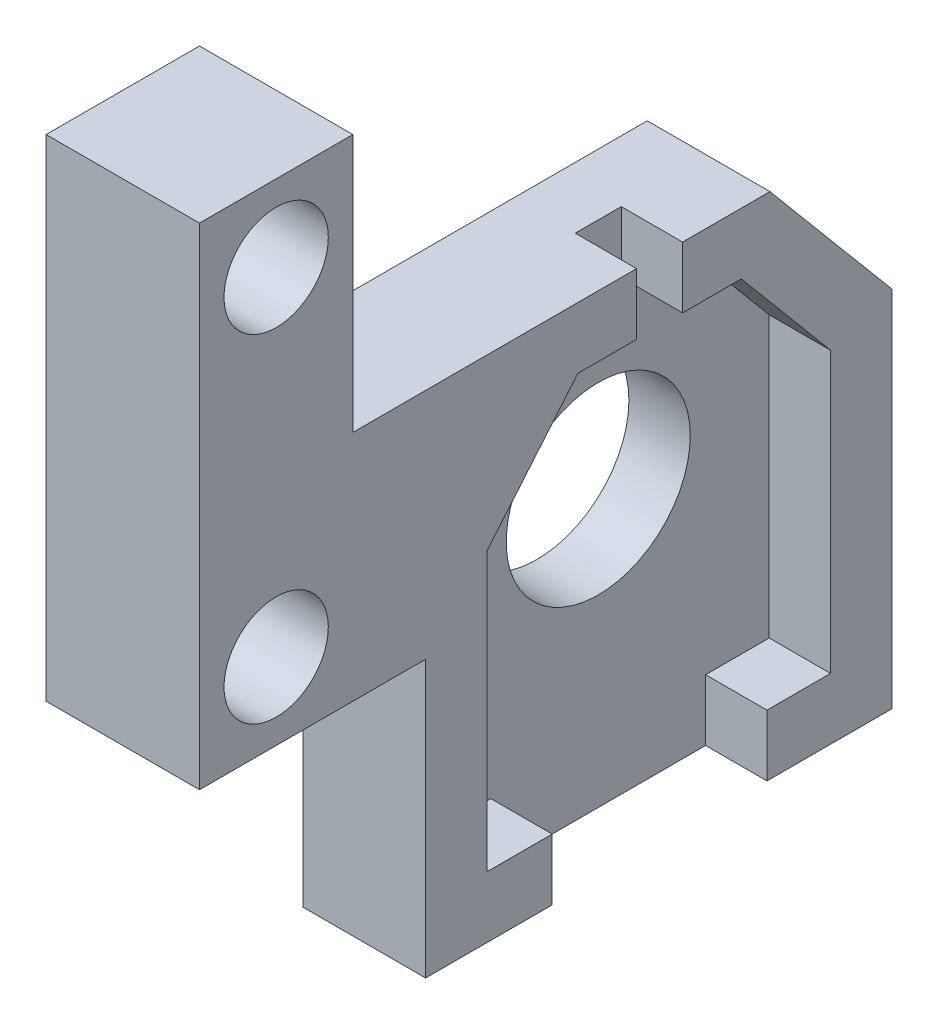
SolidWorks part; units mm, degrees
ref_plane "Front Plane" through (0, 0, 0) normal (0, 0, 1) x (1, 0, 0)
ref_plane "Top Plane" through (0, 0, 0) normal (0, 1, 0) x (1, 0, 0)
ref_plane "Right Plane" through (0, 0, 0) normal (1, 0, 0) x (0, 0, -1)
sketch "Sketch1" plane through (0, 0, 0) normal (1, 0, 0) x (0, 0, -1)
  line L0 (-6.1093, 3.9687) -> (-3.1473, 7.4987)
  line L1 (-3.1473, 7.4987) -> (-1.2321, 7.4987)
  line L2 (-6.1093, 3.9687) -> (-6.1093, -5.0913)
  line L3 (-6.1093, -5.0913) -> (-3.9821, -5.0913)
  line L4 (5.0907, 4.0335) -> (5.0907, -5.0913)
  line L5 (-4.0799, 9.4987) -> (-1.2321, 9.4987)
  line L6 (-8.1093, 4.6966) -> (-8.1093, -7.0913)
  line L7 (-8.1093, -7.0913) -> (-3.9821, -7.0913)
  line L8 (7.0907, 4.7614) -> (7.0907, -7.0913)
  line L9 (5.0907, 4.0335) -> (2.1831, 7.4987)
  line L10 (-8.1093, 4.6966) -> (-4.0799, 9.4987)
  line L11 (3.1157, 9.4987) -> (7.0907, 4.7614)
  line L12 (0.2679, 7.4987) -> (0.2679, 9.4987)
  line L13 (-1.2321, 7.4987) -> (-1.2321, 9.4987)
  line L14 (3.0179, -5.0913) -> (3.0179, -7.0913)
  line L15 (-3.9821, -5.0913) -> (-3.9821, -7.0913)
  line L16 (-0.4821, 1.9087) -> (-0.4821, -6.5913) construction
  line L17 (-8.1093, 1.9087) -> (7.0907, 1.9087) construction
  line L18 (0.2679, 9.4987) -> (3.1157, 9.4987)
  line L19 (0.2679, 7.4987) -> (2.1831, 7.4987)
  line L20 (3.0179, -5.0913) -> (5.0907, -5.0913)
  line L21 (3.0179, -7.0913) -> (7.0907, -7.0913)
  point P20 (1.2255, 7.4987)
  dimension "D1" = 2
  dimension "D2" = 2
  dimension "D3" = 2
  dimension "D4" = 2
  dimension "D5" = 2
  dimension "D6" = 2
  dimension "D7" = 40
  dimension "D8" = 40
  dimension "D9" = 3.53
  dimension "D10" = 3.5
  dimension "D11" = 7
  dimension "D12" = 3.5
  dimension "D13" = 0.75
  dimension "D14" = 0.75
  dimension "D15" = 5.59
  dimension "D16" = 11.2
sketch "Sketch2" plane through (0, 0, 0) normal (1, 0, 0) x (0, 0, -1)
  line L0 (-8.1093, -7.0913) -> (-8.1093, 4.6966)
  line L1 (-8.1093, 4.6966) -> (-4.0799, 9.4987)
  line L2 (-4.0799, 9.4987) -> (3.1157, 9.4987)
  line L3 (3.1157, 9.4987) -> (7.0907, 4.7614)
  line L4 (7.0907, 4.7614) -> (7.0907, -7.0913)
  line L5 (7.0907, -7.0913) -> (-8.1093, -7.0913)
extrude "Boss-Extrude1" add sketch "Sketch2" against normal blind 2
extrude "Boss-Extrude2" add sketch "Sketch1" along normal blind 2
sketch "Sketch3" plane through (0, 0, 0) normal (1, 0, 0) x (0, 0, -1)
  circle A0 centre (-0.4821, 1.9087) radius 3
extrude "Cut-Extrude1" cut sketch "Sketch3" against normal blind 2
sketch "Sketch4" plane through (2, 0, 0) normal (1, 0, 0) x (0, 0, -1)
  line L0 (-15.4821, 1.9087) -> (-8.1093, 1.9087)
  line L1 (-10.4821, 17.9087) -> (-15.4821, 17.9087) construction
  line L6 (-15.4821, 17.9087) -> (-15.4821, 1.9087)
  line L8 (-4.0799, 9.4987) -> (-8.1093, 4.6966)
  line L14 (-15.4821, 17.9087) -> (-10.4821, 17.9087)
  line L17 (-10.4821, 17.9087) -> (-10.4821, 9.4987)
  line L18 (-10.4821, 9.4987) -> (-4.0799, 9.4987)
  line L19 (-8.1093, 4.6966) -> (-8.1093, 1.9087)
  circle A1 centre (-12.9821, 4.4087) radius 1.7
  circle A2 centre (-12.9821, 15.4087) radius 1.7
  dimension "D7" = 3.4
  dimension "D8" = 3.4
  dimension "D1" = 2.5
  dimension "D2" = 2.5
  dimension "D3" = 2.5
  dimension "D5" = 2.5
extrude "Boss-Extrude3" add sketch "Sketch4" against normal blind 5
sketch "Sketch5" plane through (-3, 0, 0) normal (-1, 0, 0) x (0, 0, 1)
  line L0 (10.4821, 9.4987) -> (10.4821, 1.9087)
  line L1 (15.4821, 1.9087) -> (8.1093, 1.9087) construction
  line L2 (10.4821, 1.9087) -> (8.1093, 1.9087)
  line L3 (8.1093, 1.9087) -> (8.1093, 4.6966)
  line L4 (8.1093, 4.6966) -> (4.0799, 9.4987)
  line L5 (4.0799, 9.4987) -> (10.4821, 9.4987)
extrude "Cut-Extrude2" cut sketch "Sketch5" against normal blind 1
